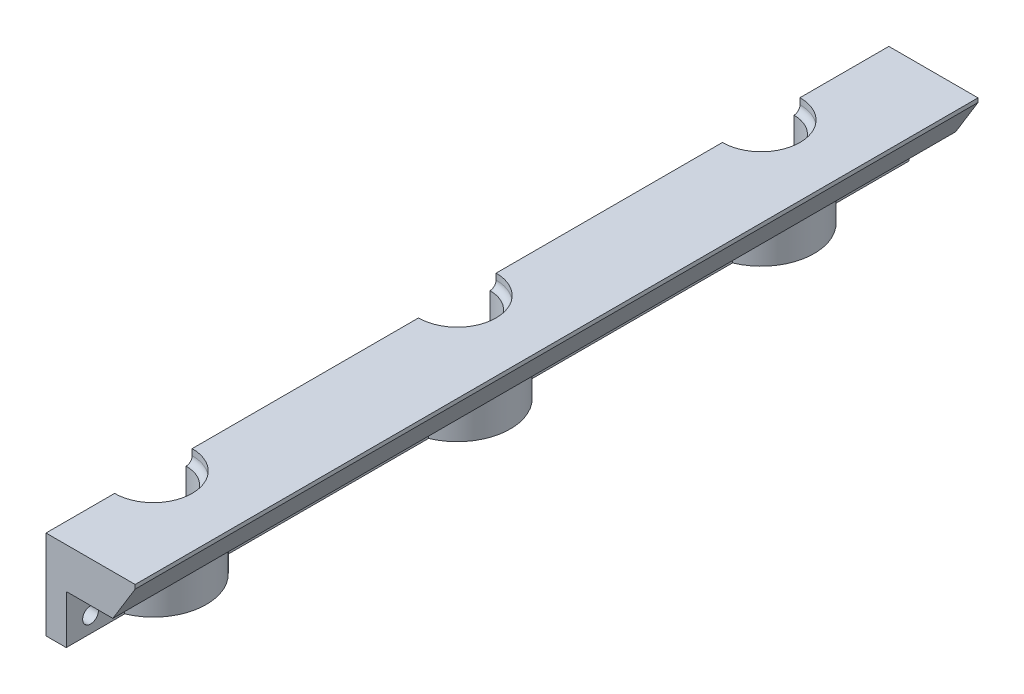
SolidWorks part; units mm, degrees
ref_plane "Płaszczyzna przednia" through (0, 0, 0) normal (0, 0, 1) x (1, 0, 0)
ref_plane "Płaszczyzna górna" through (0, 0, 0) normal (0, 1, 0) x (1, 0, 0)
ref_plane "Płaszczyzna prawa" through (0, 0, 0) normal (1, 0, 0) x (0, 0, -1)
sketch "Sketch1" plane through (0, 0, 0) normal (0, 1, 0) x (1, 0, 0)
  line L0 (0, 65.8555) -> (0, -65.8555) construction
  line L1 (0, -8.075) -> (0, -31.5)
  line L2 (0, -31.5) -> (22, -31.5)
  line L3 (104.3478, 75) -> (-104.3478, 75) construction
  line L4 (22, -31.5) -> (22, 181.5)
  line L5 (0, 158.075) -> (0, 181.5)
  line L6 (0, 181.5) -> (22, 181.5)
  line L7 (0, 8.075) -> (0, 66.925)
  line L8 (0, 83.075) -> (0, 141.925)
  arc A6 (0, -8.075) -> (0, 8.075) centre (0, 0) ccw
  arc A7 (0, 66.925) -> (0, 83.075) centre (0, 75) ccw
  arc A8 (0, 141.925) -> (0, 158.075) centre (0, 150) ccw
  point P7 (0, 0)
  point P20 (0, 75)
  point P23 (22, 75)
  dimension "D1" = 31.5
  dimension "D2" = 16.15
  dimension "D3" = 75
  dimension "D6" = 3
  dimension "D5" = 22
extrude "Boss-Extrude1" add sketch "Sketch1" against normal blind 10
sketch "Sketch3" plane through (0, -10, 0) normal (0, -1, 0) x (1, 0, 0)
  line L23 (0, -181.5) -> (0, -158.075)
  line L24 (0, -141.925) -> (0, -83.075)
  line L25 (0, -66.925) -> (0, -8.075)
  line L26 (0, 8.075) -> (0, 31.5)
  line L27 (5, -181.5) -> (5, -162.0812)
  line L28 (5, -137.9188) -> (5, -87.0812)
  line L29 (5, -62.9188) -> (5, -12.0812)
  line L30 (5, 12.0812) -> (5, 31.5)
  line L31 (5, -181.5) -> (5, -162.0812)
  line L32 (5, -137.9188) -> (5, -87.0812)
  line L33 (5, -62.9188) -> (5, -12.0812)
  line L34 (5, 12.0812) -> (5, 31.5)
  line L35 (0, 31.5) -> (5, 31.5)
  line L36 (0, -181.5) -> (5, -181.5)
  arc A15 (0, -158.075) -> (0, -141.925) centre (0, -150) ccw
  arc A16 (0, -83.075) -> (0, -66.925) centre (0, -75) ccw
  arc A17 (0, -8.075) -> (0, 8.075) centre (0, 0) ccw
  arc A18 (5, -162.0812) -> (5, -137.9188) centre (0, -150) ccw
  arc A19 (5, -87.0812) -> (5, -62.9188) centre (0, -75) ccw
  arc A20 (5, -12.0812) -> (5, 12.0812) centre (0, 0) ccw
  arc A21 (5, -162.0812) -> (5, -137.9188) centre (0, -150) ccw
  arc A22 (5, -87.0812) -> (5, -62.9188) centre (0, -75) ccw
  arc A23 (5, -12.0812) -> (5, 12.0812) centre (0, 0) ccw
  dimension "D1" = 5
extrude "Boss-Extrude2" add sketch "Sketch3" along normal blind 12
sketch "Sketch7" plane through (0, 0, 0) normal (-1, 0, 0) x (0, 0, 1)
  line L0 (-158.075, 0) -> (-171.075, 0) construction
  line L1 (-181.5, 0) -> (-158.075, 0) construction
  line L2 (-171.075, 0) -> (-171.075, -22) construction
  line L3 (-158.075, -22) -> (-181.5, -22) construction
  line L4 (-171.075, -11) -> (-158.075, -11) construction
  line L5 (-158.075, -22) -> (-158.075, 0) construction
  line L7 (-150, 0) -> (-150, -22) construction
  line L8 (-141.925, 0) -> (-158.075, 0) construction
  line L9 (-158.075, -22) -> (-141.925, -22) construction
  circle A0 centre (-170.5, -4) radius 1.95
  circle A1 centre (-170.5, -18) radius 1.95
  circle A2 centre (-129.5, -4) radius 1.95
  circle A3 centre (-129.5, -18) radius 1.95
  circle A4 centre (-95.5, -4) radius 1.95
  circle A5 centre (-54.5, -4) radius 1.95
  circle A6 centre (-54.5, -18) radius 1.95
  circle A7 centre (-95.5, -18) radius 1.95
  circle A8 centre (-20.5, -4) radius 1.95
  circle A9 centre (20.5, -4) radius 1.95
  circle A10 centre (20.5, -18) radius 1.95
  circle A11 centre (-20.5, -18) radius 1.95
  dimension "D2" = 3.9
  dimension "D3" = 4
  dimension "D4" = 3
  dimension "D1" = 13
extrude "Cut-Extrude3" cut sketch "Sketch7" against normal blind 14 and the other way blind 6
sketch "Sketch8" plane through (0, 0, 0) normal (-1, 0, 0) x (0, 0, 1)
  line L0 (-83.075, -22) -> (-141.925, -22) construction
  line L1 (-141.925, 0) -> (-112.5, -18.5) construction
  line L2 (-112.5, -18.5) -> (-83.075, 0) construction
  circle A0 centre (-112.5, -18.5) radius 1.95
  dimension "D1" = 3.9
  dimension "D2" = 3.5
extrude "Cut-Extrude4" cut sketch "Sketch8" against normal blind 4 contours A0
sketch "Sketch9" plane through (4, 0, 0) normal (-1, 0, 0) x (0, 0, 1)
  circle A0 centre (-112.5, -18.5) radius 1.5
  circle A1 centre (-112.5, -18.5) radius 1.95 construction
  dimension "D1" = 3
extrude "Cut-Extrude5" cut sketch "Sketch9" against normal blind 4
pattern_linear "LPattern1" count 2 spacing 75 along (0, 0, 1) of "Cut-Extrude4", "Cut-Extrude5"
chamfer "Chamfer2" distance 5.5 distance2 9 1 edges at (22, -10, -75)
ref_plane "Plane1" through (0, 0, -75) normal (0, 0, 1) x (1, 0, 0)
chamfer "Chamfer3" distance 7 distance2 2 3 edges at (8.075, -22, 0) (8.075, -22, -75) (8.075, -22, -150)
sketch "Sketch10" plane through (0, 0, 0) normal (-1, 0, 0) x (0, 0, 1)
  line L3 (-158.075, -15) -> (-158.075, 0) construction
  line L4 (-181.5, 0) -> (-158.075, 0) construction
  line L5 (-159.575, 1.5818) -> (-159.575, -1.5)
  line L6 (-159.575, 1.5818) -> (-158.075, 0)
  line L7 (-150, 2.1978) -> (-150, -6.9976) construction
  line L8 (-150, 2.1978) -> (-158.075, 0) construction
  line L9 (-150, 2.1978) -> (-141.925, 0) construction
  arc A0 (-159.575, -1.5) -> (-158.075, 0) centre (-158.075, -1.5) ccw
  dimension "D1" = 3
revolve "Cut-Revolve1" cut sketch "Sketch10" angle 360 about L7
pattern_linear "LPattern2" count 3 spacing 75 along (0, 0, 1) of "Cut-Revolve1"
sketch "Szkic1" plane through (0, 0, 0) normal (0, 1, 0) x (1, 0, 0)
  line L0 (0, -31.5) -> (22, -31.5) construction
  line L1 (0, -31.5) -> (22.6684, -31.5)
  line L2 (0, -31.5) -> (0, -26.5)
  line L3 (0, -26.5) -> (22.6684, -26.5)
  line L4 (22.6684, -31.5) -> (22.6684, -26.5)
extrude "Wytnij-wyciągnięcie1" cut sketch "Szkic1" against normal blind 30.5
